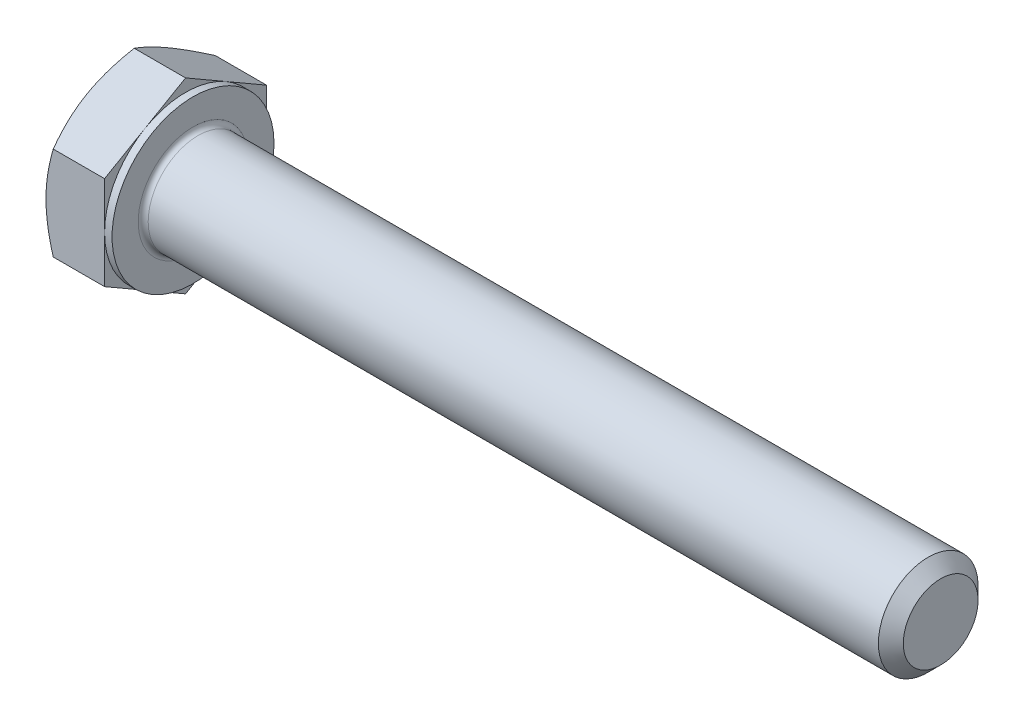
SolidWorks part; units mm, degrees
extrude "基体-拉伸" add sketch "草图1" along normal blind 5.3
sketch "草图1" plane through (0, 0, 0) normal (1, 0, 0) x (0, 0, -1)
  line L0 (6.5, 3.7528) -> (6.5, -3.7528)
  line L1 (-6.5, 3.7528) -> (-6.5, -3.7528)
  line L2 (6.5, -3.7528) -> (0, -7.5056)
  line L3 (0, -7.5056) -> (-6.5, -3.7528)
  line L4 (6.5, 3.7528) -> (0, 7.5056)
  line L5 (0, 7.5056) -> (-6.5, 3.7528)
  dimension "s" = 13
  dimension "D2" = 120
  dimension "D3" = 6.5
  dimension "D4" = 6.5
  dimension "D5" = 6.5
revolve "切除-旋转1" cut sketch "草图3" angle 360 about L6
sketch "草图3" plane through (0, 0, 0) normal (0, 0, 1) x (1, 0, 0)
  line L0 (0, 6.5) -> (3.4673, 12.5056)
  line L1 (0, 7.5056) -> (0, 3.7528) construction
  line L2 (3.4673, 12.5056) -> (3.4673, 17.5056)
  line L3 (3.4673, 17.5056) -> (-10, 17.5056)
  line L4 (-10, 17.5056) -> (-10, 6.5)
  line L5 (-10, 6.5) -> (0, 6.5)
  line L6 (0, 0) -> (99.06, 0) construction
  line L7 (5.3, 7.5056) -> (0, 7.5056) construction
  dimension "D1" = 6.5
  dimension "D2" = 5
  dimension "D3" = 10
  dimension "D4" = 5
  dimension "Head_ch_ang" = 30
material "3.6级"
ref_plane "前视" through (0, 0, 0) normal (0, 0, 1) x (1, 0, 0)
ref_plane "上视" through (0, 0, 0) normal (0, 1, 0) x (1, 0, 0)
ref_plane "右视" through (0, 0, 0) normal (1, 0, 0) x (0, 0, -1)
sketch "草图2" plane through (0, 0, 0) normal (0, 0, 1) x (1, 0, 0)
  line L0 (0, 3.7528) -> (0, -3.7528) construction
  line L1 (0, 0) -> (65.3, 0)
  line L2 (0, 0) -> (0, 4)
  line L3 (0, 4) -> (27.8072, 4)
  line L4 (65.3, 0) -> (65.3, 2.9175)
  line L5 (5.3, 7.5056) -> (5.3, 3.7528) construction
  line L7 (0, 0) -> (96.52, 0) construction
  line L8 (65.3, -2.9175) -> (27.8072, -4) construction
  line L9 (0, -4) -> (27.8072, -4) construction
  line L10 (6.55, 15.24) -> (6.55, -1.27) construction
  line L11 (43.3, 15.24) -> (43.3, -1.27) construction
  line L12 (5.3, 3.7528) -> (5.3, -3.7528) construction
  line L13 (27.8072, 4) -> (65.3, 4)
  line L14 (65.3, 4) -> (65.3, 2.9175)
revolve "凸台-旋转1" add sketch "草图2" angle 360 about L7
cosmetic thread "螺旋线1" parameters "Thread_length"=22, "Thread_minor"=5.835
sketch "草图5" plane through (0, 0, 0) normal (0, 0, 1) x (1, 0, 0)
  line L0 (5.3, 6.5) -> (1.8327, 12.5056)
  line L1 (5.3, 7.5056) -> (5.3, 3.7528) construction
  line L2 (1.8327, 12.5056) -> (1.8327, 17.5056)
  line L3 (1.8327, 17.5056) -> (11.8327, 17.5056)
  line L4 (11.8327, 17.5056) -> (11.8327, 6.5)
  line L5 (11.8327, 6.5) -> (5.3, 6.5)
  line L7 (5.3, 7.5056) -> (0.5806, 7.5056) construction
  line L8 (0, 0) -> (99.06, 0) construction
  line L9 (0, 0) -> (99.06, 0) construction
  dimension "D1" = 6.5
  dimension "D2" = 5
  dimension "D3" = 10
  dimension "D4" = 5
  dimension "Head_ch_ang" = 30
revolve "切除-旋转2" cut sketch "草图5" angle 360 about L8
sketch "草图4" plane through (0, 0, 0) normal (0, 0, 1) x (1, 0, 0)
  line L1 (5.3, 7.5056) -> (5.3, 3.7528) construction
  line L2 (5.3, 6.5) -> (4.7, 6.5)
  line L3 (5.3, 6.5) -> (5.3, 17.5056)
  line L4 (5.3, 17.5056) -> (4.7, 17.5056)
  line L5 (0, 0) -> (95.25, 0) construction
  line L6 (0, 0) -> (96.52, 0) construction
  line L7 (4.7, 6.5) -> (4.7, 17.5056)
  line L8 (4.7194, 7.5056) -> (0.5806, 7.5056) construction
  dimension "D2" = 10
  dimension "D1" = 13
revolve "切除-旋转3" cut sketch "草图4" angle 360 about L5
chamfer "倒角" distance 1 angle 45 1 edges at (65.3, 0, 4)
fillet "圆角" radius 0.4 1 edges at (5.3, 0, -4)
sketch "草图6" plane through (0, 0, 0) normal (0, 0, 1) x (1, 0, 0)
  line L0 (43.3, -2.9175) -> (42.675, -4)
  line L1 (43.3, -2.9175) -> (43.925, -4)
  line L2 (43.925, -4) -> (43.925, -5)
  line L3 (-3.175, 0) -> (5.1513, 0) construction
  line L5 (43.925, -5) -> (42.675, -5)
  line L6 (42.675, -5) -> (42.675, -4)
  dimension "Thread_minor" = 5.835
  dimension "Diameter" = 8
  dimension "Start" = 43.3
revolve "切除-旋转4" [suppressed] cut sketch "草图6" angle 360 about L3
pattern_linear "阵列(线性)1" [suppressed]
equation "\"D3@草图1\" = \"s@草图1\" / 2"
equation "\"D4@草图1\" = \"D3@草图1\""
equation "\"D5@草图1\" = \"D4@草图1\""
equation "\"Thread_minor@螺旋线1\" = \"Minor_dia@草图2\""
equation "\"D1@草图3\" = \"s@草图1\" / 2"
equation "\"D1@草图5\" = \"s@草图1\" / 2"
equation "\"Head_ch_ang@草图5\" = \"Head_ch_ang@草图3\""
equation "\"D1@草图4\" = \"s@草图1\""
equation "\"Thread_length@螺旋线1\" = ((sgn( (\"l@草图2\" - \"p@草图2\" ) - \"h@草图2\" )-1)*( (\"l@草图2\" - \"p@草图2\" ) - \"h@草图2\" ))/-2+ \"h@草图2\""
equation "\"Thread_minor@草图6\" = \"Minor_dia@草图2\""
equation "\"Diameter@草图6\" = \"m@草图2\""
equation "\"Overcut@草图6\" = \"m@草图2\" * 1.25"
equation "\"Start@草图6\" = \"k@基体-拉伸\" + \"l@草图2\" - \"Thread_length@螺旋线1\"  '---Non-countersunk---"
equation "\"Num_threads@阵列(线性)1\" = int( \"Thread_length@螺旋线1\" / \"p@草图2\" + 0.999 )  + 1"
equation "\"Advance@阵列(线性)1\" = \"Thread_length@螺旋线1\" /  (\"Num_threads@阵列(线性)1\" - 1) 'relax it"
equation "\"Num_threads@阵列(线性)1\" = \"Num_threads@阵列(线性)1\" - sgn( \"Num_threads@阵列(线性)1\" - 1) '---chamfered tips only---"
equation "\"Minor_dia@草图2\" = \"m@草图2\"-\"p@草图2\" * 1.732"
equation "\"D1@倒角\" = \"p@草图2\"*0.8"
